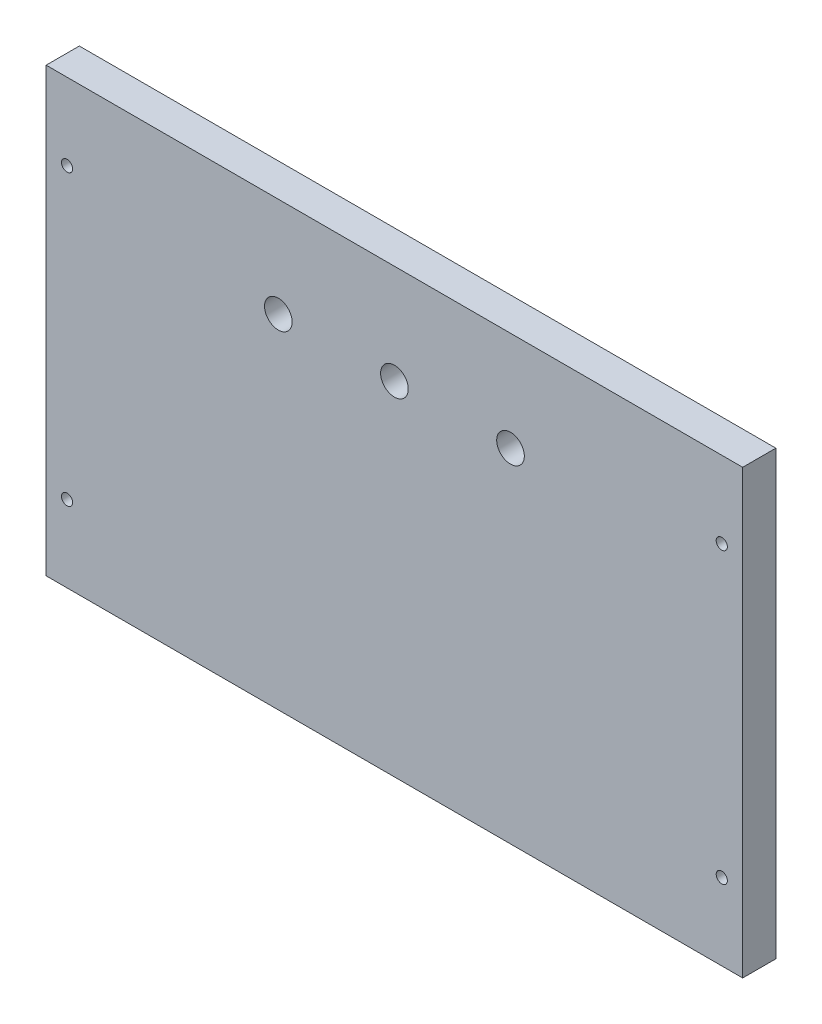
SolidWorks part; units mm, degrees
ref_plane "Front Plane" through (0, 0, 0) normal (0, 0, 1) x (1, 0, 0)
ref_plane "Top Plane" through (0, 0, 0) normal (0, 1, 0) x (1, 0, 0)
ref_plane "Right Plane" through (0, 0, 0) normal (1, 0, 0) x (0, 0, -1)
sketch "Sketch1" plane through (0, 0, 0) normal (0, 0, 1) x (1, 0, 0)
  line L0 (100, 127) -> (100, 98.425) construction
  line L1 (0, 0) -> (200, 0)
  line L2 (0, 0) -> (0, 127)
  line L3 (0, 127) -> (200, 127)
  line L4 (200, 0) -> (200, 127)
  line L5 (66.6667, 127) -> (66.6667, 98.425) construction
  line L6 (133.3333, 127) -> (133.3333, 98.425) construction
  circle A0 centre (66.6667, 98.425) radius 3.9687
  circle A1 centre (100, 98.425) radius 3.9687
  circle A2 centre (133.3333, 98.425) radius 3.9687
  circle A3 centre (6, 105) radius 1.6
  circle A4 centre (6, 22) radius 1.6
  circle A5 centre (194, 22) radius 1.6
  circle A6 centre (194, 105) radius 1.6
  dimension "D3" = 7.9375
  dimension "D4" = 7.9375
  dimension "D5" = 7.9375
  dimension "D11" = 3.2
  dimension "D14" = 3.2
  dimension "D17" = 3.2
  dimension "D22" = 3.2
  dimension "D1" = 127
  dimension "D2" = 200
  dimension "D6" = 28.575
  dimension "D7" = 28.575
  dimension "D8" = 28.575
  dimension "D9" = 66.6667
  dimension "D10" = 66.6667
  dimension "D12" = 6
  dimension "D13" = 22
  dimension "D15" = 6
  dimension "D16" = 22
  dimension "D18" = 6
  dimension "D19" = 22
  dimension "D20" = 6
  dimension "D21" = 22
extrude "Boss-Extrude1" add sketch "Sketch1" along normal blind 9.525
equation "\"Length\"= 283mm"
equation "\"Width\"= 225mm"
equation "\"WallThickness\"= 12.5mm"
equation "\"UpperWaterJacketThickness\"= 28mm"
equation "\"SpacerHeight\"= 80.2mm"
equation "\"SpacerCornerWidth\"= 10mm"
equation "\"SpacerCornerHeight\"= 60.16mm"
equation "\"SpacerPegDiameter\"= 10mm"
equation "\"SpacerPegHeight\"= 10mm"
equation "\"TubingShort\"= 110mm"
equation "\"TubingLong\"= 175mm"
equation "\"PlateLength\"= 252mm"
equation "\"PlateWidth\"= 190mm"
equation "\"PlateHoleDiameter\"= 5.9mm"
equation "\"PlateHoleBottom\"= 2mm"
equation "\"PlateHoleSide\"= 1.55mm"
equation "\"PlateHoleSpacing\"= 3.1mm"
equation "\"PlateThickness\"= 1.55mm"
equation "\"ReservoirBottom\"= 12.5mm"
equation "\"ReservoirSupportWidth\"= 12mm"
equation "\"ReservoirSupportHeight\"= 15.1mm"
equation "\"ReservoirSupportPlacementHeight\"= 50mm"
equation "\"ReservoirHoleDiameter\"= 12.7mm"
equation "\"ReservoirHoleRight\"= 25mm"
equation "\"ReservoirHoleTop\"= \"ReservoirSupportPlacementHeight\""
equation "\"ReservoirHeight\"= 90mm"
equation "\"ReservoirPortBottom\"= 4mm"
equation "\"ReservoirPortTop\"= 10mm"
equation "\"ReservoirPortWidth\"= 101mm"
equation "\"CustomSpacerWallThickness\"= 0.375in"
equation "\"CustomSpacerHeight\"= 5in"
equation "\"CustomSpacerRodHoleHeight\"= .75in"
equation "\"CustomSpacerRodHoleDiameter\"= .3125in"
equation "\"ScrewBlockSide\"= 12mm"
equation "\"ScrewBlockUpperHeight\"= 16mm"
equation "\"ScrewBlockLowerHeight\"= 16mm"
equation "\"InternalLength\"= \"Length\" - ( 2 * \"WallThickness\" )"
equation "\"InternalWidth\"= \"Width\" - ( 2 * \"WallThickness\" )"
equation "\"CustomSpacerPegHeight\"= 1in"
equation "\"CustomSpacerScrewBore\"=3.2mm"
equation "\"CustomSpacerScrewDepth\"=10mm"
equation "\"D1@Sketch1\"=\"CustomSpacerHeight\""
equation "\"D2@Sketch1\"=\"InternalWidth\""
equation "\"D3@Sketch1\"=\"CustomSpacerRodHoleDiameter\""
equation "\"D4@Sketch1\"=\"CustomSpacerRodHoleDiameter\""
equation "\"D5@Sketch1\"=\"CustomSpacerRodHoleDiameter\""
equation "\"D6@Sketch1\"=\"CustomSpacerRodHoleHeight\"+\"CustomSpacerRodHoleDiameter\"+0.0625in"
equation "\"D7@Sketch1\"=\"CustomSpacerRodHoleHeight\"+\"CustomSpacerRodHoleDiameter\"+0.0625in"
equation "\"D8@Sketch1\"=\"CustomSpacerRodHoleHeight\"+\"CustomSpacerRodHoleDiameter\"+0.0625in"
equation "\"D9@Sketch1\"=\"InternalWidth\"/3"
equation "\"D10@Sketch1\"=\"InternalWidth\"/3"
equation "\"D11@Sketch1\"=\"CustomSpacerScrewBore\""
equation "\"D12@Sketch1\"=\"ScrewBlockSide\"/2"
equation "\"D13@Sketch1\"=\"ScrewBlockUpperHeight\"+\"ScrewBlockSide\"/2"
equation "\"D14@Sketch1\"=\"CustomSpacerScrewBore\""
equation "\"D15@Sketch1\"=\"ScrewBlockSide\"/2"
equation "\"D16@Sketch1\"=\"ScrewBlockLowerHeight\"+\"ScrewBlockSide\"/2"
equation "\"D17@Sketch1\"=\"CustomSpacerScrewBore\""
equation "\"D18@Sketch1\"=\"ScrewBlockSide\"/2"
equation "\"D19@Sketch1\"=\"ScrewBlockUpperHeight\"+\"ScrewBlockSide\"/2"
equation "\"D20@Sketch1\"=\"ScrewBlockSide\"/2"
equation "\"D21@Sketch1\"=\"ScrewBlockLowerHeight\"+\"ScrewBlockSide\"/2"
equation "\"D22@Sketch1\"=\"CustomSpacerScrewBore\""
equation "\"D1@Boss-Extrude1\"=\"CustomSpacerWallThickness\""
